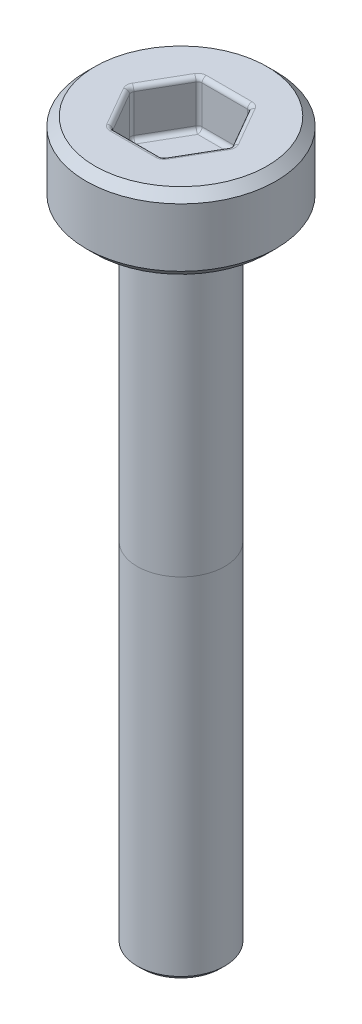
SolidWorks part; units mm, degrees
ref_plane "Front Plane" through (0, 0, 0) normal (0, 0, 1) x (1, 0, 0)
ref_plane "Top Plane" through (0, 0, 0) normal (0, 1, 0) x (1, 0, 0)
ref_plane "Right Plane" through (0, 0, 0) normal (1, 0, 0) x (0, 0, -1)
sketch "Sketch1" plane through (0, 0, 0) normal (0, 1, 0) x (1, 0, 0)
  circle A0 centre (0, 0) radius 0.75
  dimension "D1" = 1.5
extrude "Boss-Extrude1" add sketch "Sketch1" along normal blind 11
sketch "Sketch2" plane through (0, 11, 0) normal (0, 1, 0) x (1, 0, 0)
  circle A0 centre (0, 0) radius 1.625
  dimension "D1" = 3.25
extrude "Boss-Extrude2" add sketch "Sketch2" along normal blind 1.3
fillet "Fillet1" radius 0.15 1 edges at (0, 11, 0.75)
chamfer "Chamfer1" distance 0.15 angle 45 2 edges at (0, 12.3, 1.625) (0, 11, 1.625)
sketch "Sketch3" plane through (0, 12.3, 0) normal (0, 1, 0) x (1, 0, 0)
  line L1 (-0.433, 0.75) -> (-0.866, 0)
  line L2 (-0.866, 0) -> (-0.433, -0.75)
  line L3 (-0.433, -0.75) -> (0.433, -0.75)
  line L4 (0.433, -0.75) -> (0.866, 0)
  line L5 (0.866, 0) -> (0.433, 0.75)
  line L6 (0.433, 0.75) -> (-0.433, 0.75)
  circle A0 centre (0, 0) radius 0.75 construction
  dimension "D1" = 1.5
extrude "Cut-Extrude1" cut sketch "Sketch3" against normal blind 0.8
chamfer "Chamfer2" distance 0.075 angle 45 1 edges at (0, 0, 0.75)
fillet "Fillet2" radius 0.075 18 edges at (0, 12.3, -0.75) (-0.6495, 12.3, -0.375) (-0.6495, 12.3, 0.375) (0, 12.3, 0.75) (0.6495, 12.3, 0.375) (0.6495, 12.3, -0.375) (-0.6495, 11.5, -0.375) (-0.6495, 11.5, 0.375) (0, 11.5, 0.75) (0.6495, 11.5, 0.375) (0.6495, 11.5, -0.375) (-0.433, 11.9, -0.75) (-0.866, 11.9, 0) (-0.433, 11.9, 0.75) (0.433, 11.9, 0.75) (0.866, 11.9, 0) (0.433, 11.9, -0.75) (0, 11.5, -0.75)
sketch "Sketch4" plane through (0, 0, 0) normal (0, 0, 1) x (1, 0, 0)
  line L0 (-5.6741, 6) -> (6.8738, 6)
  dimension "D1" = 6
split line "Split Line1"
